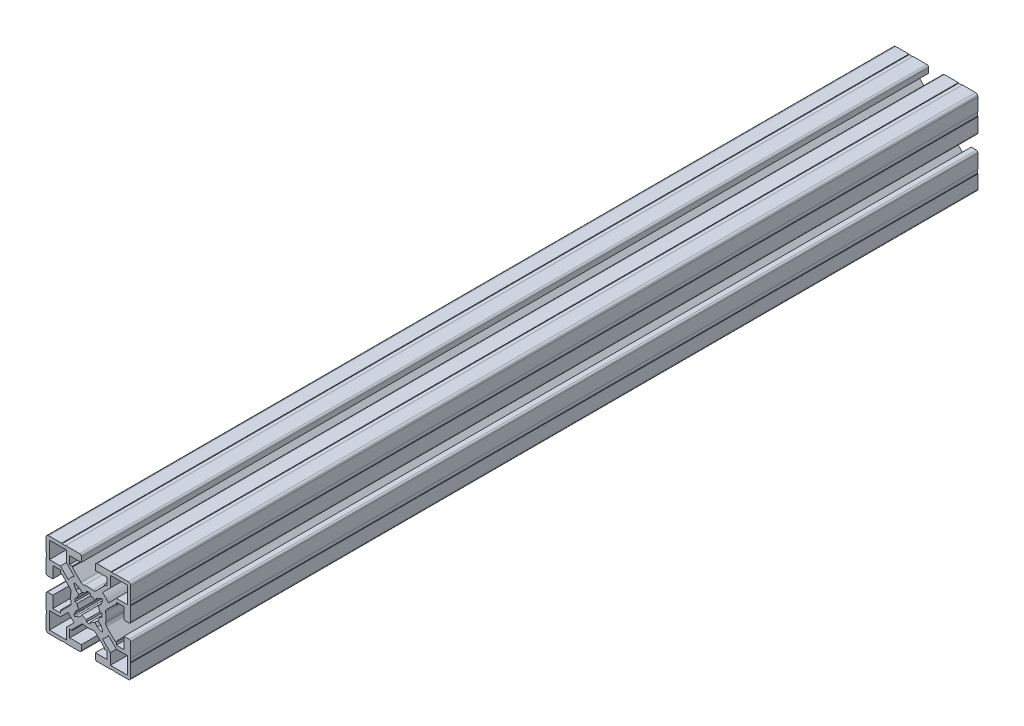
SolidWorks part; units mm, degrees
ref_plane "Plano frontal" through (0, 0, 0) normal (0, 0, 1) x (1, 0, 0)
ref_plane "Plano superior" through (0, 0, 0) normal (0, 1, 0) x (1, 0, 0)
ref_plane "Plano direito" through (0, 0, 0) normal (1, 0, 0) x (0, 0, -1)
sketch "Model" plane through (0, 0, 0) normal (0, 0, 1) x (1, 0, 0)
  line L64 (-23.5, -25) -> (-15.8, -25)
  line L65 (-15.8, -25) -> (-15.6, -24.8)
  line L66 (-15.6, -24.8) -> (-13.6, -24.8)
  line L67 (-13.6, -24.8) -> (-13.4, -25)
  line L68 (-13.4, -25) -> (-5.15, -25)
  line L69 (-4.15, -24) -> (-4.15, -21)
  line L70 (-4.15, -21) -> (-11, -21)
  line L71 (-11, -21) -> (-11, -16.464)
  line L72 (-11, -16.464) -> (-9.5, -16.464)
  line L73 (-9.5, -16.464) -> (-9.5, -15.864)
  line L74 (-9.5, -15.864) -> (-4.3679, -10.7318)
  line L75 (4.3679, -10.7318) -> (9.5, -15.864)
  line L76 (9.5, -15.864) -> (9.5, -16.464)
  line L77 (9.5, -16.464) -> (11, -16.464)
  line L78 (11, -16.464) -> (11, -21)
  line L79 (11, -21) -> (4.15, -21)
  line L80 (4.15, -21) -> (4.15, -24)
  line L81 (5.15, -25) -> (13.4, -25)
  line L82 (13.4, -25) -> (13.6, -24.8)
  line L83 (13.6, -24.8) -> (15.6, -24.8)
  line L84 (15.6, -24.8) -> (15.8, -25)
  line L85 (15.8, -25) -> (23.5, -25)
  line L86 (25, -23.5) -> (25, -15.8)
  line L87 (25, -15.8) -> (24.8, -15.6)
  line L88 (24.8, -15.6) -> (24.8, -13.6)
  line L89 (24.8, -13.6) -> (25, -13.4)
  line L90 (25, -13.4) -> (25, -5.15)
  line L91 (24, -4.15) -> (21, -4.15)
  line L92 (21, -4.15) -> (21, -11)
  line L93 (21, -11) -> (16.464, -11)
  line L94 (16.464, -11) -> (16.464, -9.5)
  line L95 (16.464, -9.5) -> (15.864, -9.5)
  line L96 (15.864, -9.5) -> (10.7318, -4.3679)
  line L97 (10.7318, 4.3679) -> (15.864, 9.5)
  line L98 (15.864, 9.5) -> (16.464, 9.5)
  line L99 (16.464, 9.5) -> (16.464, 11)
  line L100 (16.464, 11) -> (21, 11)
  line L101 (21, 11) -> (21, 4.15)
  line L102 (21, 4.15) -> (24, 4.15)
  line L103 (25, 5.15) -> (25, 13.4)
  line L104 (25, 13.4) -> (24.8, 13.6)
  line L105 (24.8, 13.6) -> (24.8, 15.6)
  line L106 (24.8, 15.6) -> (25, 15.8)
  line L107 (25, 15.8) -> (25, 23.5)
  line L108 (23.5, 25) -> (15.8, 25)
  line L109 (15.8, 25) -> (15.6, 24.8)
  line L110 (15.6, 24.8) -> (13.6, 24.8)
  line L111 (13.6, 24.8) -> (13.4, 25)
  line L112 (13.4, 25) -> (5.15, 25)
  line L113 (4.15, 24) -> (4.15, 21)
  line L114 (4.15, 21) -> (11, 21)
  line L115 (11, 21) -> (11, 16.464)
  line L116 (11, 16.464) -> (9.5, 16.464)
  line L117 (9.5, 16.464) -> (9.5, 15.864)
  line L118 (9.5, 15.864) -> (4.3679, 10.7318)
  line L119 (-4.3679, 10.7318) -> (-9.5, 15.864)
  line L120 (-9.5, 15.864) -> (-9.5, 16.464)
  line L121 (-9.5, 16.464) -> (-11, 16.464)
  line L122 (-11, 16.464) -> (-11, 21)
  line L123 (-11, 21) -> (-4.15, 21)
  line L124 (-4.15, 21) -> (-4.15, 24)
  line L125 (-5.15, 25) -> (-13.4, 25)
  line L126 (-13.4, 25) -> (-13.6, 24.8)
  line L127 (-13.6, 24.8) -> (-15.6, 24.8)
  line L128 (-15.6, 24.8) -> (-15.8, 25)
  line L129 (-15.8, 25) -> (-23.5, 25)
  line L130 (-25, 23.5) -> (-25, 15.8)
  line L131 (-25, 15.8) -> (-24.8, 15.6)
  line L132 (-24.8, 15.6) -> (-24.8, 13.6)
  line L133 (-24.8, 13.6) -> (-25, 13.4)
  line L134 (-25, 13.4) -> (-25, 5.15)
  line L135 (-24, 4.15) -> (-21, 4.15)
  line L136 (-21, 4.15) -> (-21, 11)
  line L137 (-21, 11) -> (-16.464, 11)
  line L138 (-16.464, 11) -> (-16.464, 9.5)
  line L139 (-16.464, 9.5) -> (-15.864, 9.5)
  line L140 (-15.864, 9.5) -> (-10.7318, 4.3679)
  line L141 (-10.7318, -4.3679) -> (-15.864, -9.5)
  line L142 (-15.864, -9.5) -> (-16.464, -9.5)
  line L143 (-16.464, -9.5) -> (-16.464, -11)
  line L144 (-16.464, -11) -> (-21, -11)
  line L145 (-21, -11) -> (-21, -4.15)
  line L146 (-21, -4.15) -> (-24, -4.15)
  line L147 (-25, -5.15) -> (-25, -13.4)
  line L148 (-25, -13.4) -> (-24.8, -13.6)
  line L149 (-24.8, -13.6) -> (-24.8, -15.6)
  line L150 (-24.8, -15.6) -> (-25, -15.8)
  line L151 (-25, -15.8) -> (-25, -23.5)
  line L152 (11.8673, 8.3317) -> (16.5355, 13)
  line L153 (16.5355, 13) -> (23, 13)
  line L154 (23, 13) -> (23, 23)
  line L155 (23, 23) -> (13, 23)
  line L156 (13, 23) -> (13, 16.5355)
  line L157 (13, 16.5355) -> (8.3317, 11.8673)
  line L158 (-13, 23) -> (-13, 16.5355)
  line L159 (-13, 16.5355) -> (-8.3317, 11.8673)
  line L160 (-11.8673, 8.3317) -> (-16.5355, 13)
  line L161 (-16.5355, 13) -> (-23, 13)
  line L162 (-23, 13) -> (-23, 23)
  line L163 (-23, 23) -> (-13, 23)
  line L164 (-13, -23) -> (-23, -23)
  line L165 (-23, -23) -> (-23, -13)
  line L166 (-23, -13) -> (-16.5355, -13)
  line L167 (-16.5355, -13) -> (-11.8673, -8.3317)
  line L168 (-8.3317, -11.8673) -> (-13, -16.5355)
  line L169 (-13, -16.5355) -> (-13, -23)
  line L170 (8.3317, -11.8673) -> (13, -16.5355)
  line L171 (13, -16.5355) -> (13, -23)
  line L172 (13, -23) -> (23, -23)
  line L173 (23, -23) -> (23, -13)
  line L174 (23, -13) -> (16.5355, -13)
  line L175 (16.5355, -13) -> (11.8673, -8.3317)
  line L176 (-7.7694, -8.4227) -> (-5.1887, -7.3537)
  line L177 (-5.1887, -7.3537) -> (-3.8785, -5.6462)
  line L178 (-1.25, -6.735) -> (-1.0933, -7.9249)
  line L179 (1.0933, -7.9249) -> (1.25, -6.735)
  line L180 (3.8785, -5.6462) -> (5.1887, -7.3537)
  line L181 (5.1887, -7.3537) -> (7.7694, -8.4227)
  line L182 (8.4227, -7.7694) -> (7.3537, -5.1887)
  line L183 (7.3537, -5.1887) -> (5.6462, -3.8785)
  line L184 (6.735, -1.25) -> (7.9249, -1.0933)
  line L185 (7.9249, 1.0933) -> (6.735, 1.25)
  line L186 (5.6462, 3.8785) -> (7.3537, 5.1887)
  line L187 (7.3537, 5.1887) -> (8.4227, 7.7694)
  line L188 (7.7694, 8.4227) -> (5.1887, 7.3537)
  line L189 (5.1887, 7.3537) -> (3.8785, 5.6462)
  line L190 (1.25, 6.735) -> (1.0933, 7.9249)
  line L191 (-1.0933, 7.9249) -> (-1.25, 6.735)
  line L192 (-3.8785, 5.6462) -> (-5.1887, 7.3537)
  line L193 (-5.1887, 7.3537) -> (-7.7694, 8.4227)
  line L194 (-8.4227, 7.7694) -> (-7.3537, 5.1887)
  line L195 (-7.3537, 5.1887) -> (-5.6462, 3.8785)
  line L196 (-6.735, 1.25) -> (-7.9249, 1.0933)
  line L197 (-7.9249, -1.0933) -> (-6.735, -1.25)
  line L198 (-5.6462, -3.8785) -> (-7.3537, -5.1887)
  line L199 (-7.3537, -5.1887) -> (-8.4227, -7.7694)
  line L342 (0, 8.8704) -> (0, 13.9613) construction
  line L343 (13.42, 0) -> (6.735, 0) construction
  line L345 (3.8417, 0) -> (-2.8013, 0) construction
  line L346 (-3.8827, 0) -> (-8.9809, 0) construction
  line L347 (-10.5, 0) -> (-14.388, 0) construction
  line L350 (0, -4.7052) -> (0, 6.735) construction
  line L351 (0, -12.2643) -> (0, -5.7851) construction
  arc A53 (-5.15, -25) -> (-4.15, -24) centre (-5.15, -24) ccw
  arc A54 (-2.4811, -10.2027) -> (-4.3679, -10.7318) centre (-2.9536, -12.146) ccw
  arc A55 (-2.4811, -10.2027) -> (2.4811, -10.2027) centre (0, 0) ccw
  arc A56 (4.3679, -10.7318) -> (2.4811, -10.2027) centre (2.9536, -12.146) ccw
  arc A57 (4.15, -24) -> (5.15, -25) centre (5.15, -24) ccw
  arc A58 (23.5, -25) -> (25, -23.5) centre (23.5, -23.5) ccw
  arc A59 (25, -5.15) -> (24, -4.15) centre (24, -5.15) ccw
  arc A60 (10.2027, -2.4811) -> (10.7318, -4.3679) centre (12.146, -2.9536) ccw
  arc A61 (10.2027, -2.4811) -> (10.2027, 2.4811) centre (0, 0) ccw
  arc A62 (10.7318, 4.3679) -> (10.2027, 2.4811) centre (12.146, 2.9536) ccw
  arc A63 (24, 4.15) -> (25, 5.15) centre (24, 5.15) ccw
  arc A64 (25, 23.5) -> (23.5, 25) centre (23.5, 23.5) ccw
  arc A65 (5.15, 25) -> (4.15, 24) centre (5.15, 24) ccw
  arc A66 (2.4811, 10.2027) -> (4.3679, 10.7318) centre (2.9536, 12.146) ccw
  arc A67 (2.4811, 10.2027) -> (-2.4811, 10.2027) centre (0, 0) ccw
  arc A68 (-4.3679, 10.7318) -> (-2.4811, 10.2027) centre (-2.9536, 12.146) ccw
  arc A69 (-4.15, 24) -> (-5.15, 25) centre (-5.15, 24) ccw
  arc A70 (-23.5, 25) -> (-25, 23.5) centre (-23.5, 23.5) ccw
  arc A71 (-25, 5.15) -> (-24, 4.15) centre (-24, 5.15) ccw
  arc A72 (-10.2027, 2.4811) -> (-10.7318, 4.3679) centre (-12.146, 2.9536) ccw
  arc A73 (-10.2027, 2.4811) -> (-10.2027, -2.4811) centre (0, 0) ccw
  arc A74 (-10.7318, -4.3679) -> (-10.2027, -2.4811) centre (-12.146, -2.9536) ccw
  arc A75 (-24, -4.15) -> (-25, -5.15) centre (-24, -5.15) ccw
  arc A76 (-25, -23.5) -> (-23.5, -25) centre (-23.5, -23.5) ccw
  arc A77 (11.8673, 8.3317) -> (8.3317, 11.8673) centre (0, 0) ccw
  arc A78 (-8.3317, 11.8673) -> (-11.8673, 8.3317) centre (0, 0) ccw
  arc A79 (-11.8673, -8.3317) -> (-8.3317, -11.8673) centre (0, 0) ccw
  arc A80 (8.3317, -11.8673) -> (11.8673, -8.3317) centre (0, 0) ccw
  arc A81 (-8.3143, -8.3143) -> (-7.7694, -8.4227) centre (-7.9608, -7.9608) ccw
  arc A82 (-3.8785, -5.6462) -> (-1.25, -6.735) centre (0, 0) ccw
  arc A83 (-1.0933, -7.9249) -> (1.0933, -7.9249) centre (0, 0) ccw
  arc A84 (1.25, -6.735) -> (3.8785, -5.6462) centre (0, 0) ccw
  arc A85 (7.7694, -8.4227) -> (8.4227, -7.7694) centre (7.9608, -7.9608) ccw
  arc A86 (5.6462, -3.8785) -> (6.735, -1.25) centre (0, 0) ccw
  arc A87 (7.9249, -1.0933) -> (7.9249, 1.0933) centre (0, 0) ccw
  arc A88 (6.735, 1.25) -> (5.6462, 3.8785) centre (0, 0) ccw
  arc A89 (8.4227, 7.7694) -> (7.7694, 8.4227) centre (7.9608, 7.9608) ccw
  arc A90 (3.8785, 5.6462) -> (1.25, 6.735) centre (0, 0) ccw
  arc A91 (1.0933, 7.9249) -> (-1.0933, 7.9249) centre (0, 0) ccw
  arc A92 (-1.25, 6.735) -> (-3.8785, 5.6462) centre (0, 0) ccw
  arc A93 (-7.7694, 8.4227) -> (-8.4227, 7.7694) centre (-7.9608, 7.9608) ccw
  arc A94 (-5.6462, 3.8785) -> (-6.735, 1.25) centre (0, 0) ccw
  arc A95 (-7.9249, 1.0933) -> (-7.9249, -1.0933) centre (0, 0) ccw
  arc A96 (-6.735, -1.25) -> (-5.6462, -3.8785) centre (0, 0) ccw
  arc A97 (-8.4227, -7.7694) -> (-8.3143, -8.3143) centre (-7.9608, -7.9608) ccw
extrude "Ressalto-extrusão1" add sketch "Model" along normal blind 500
